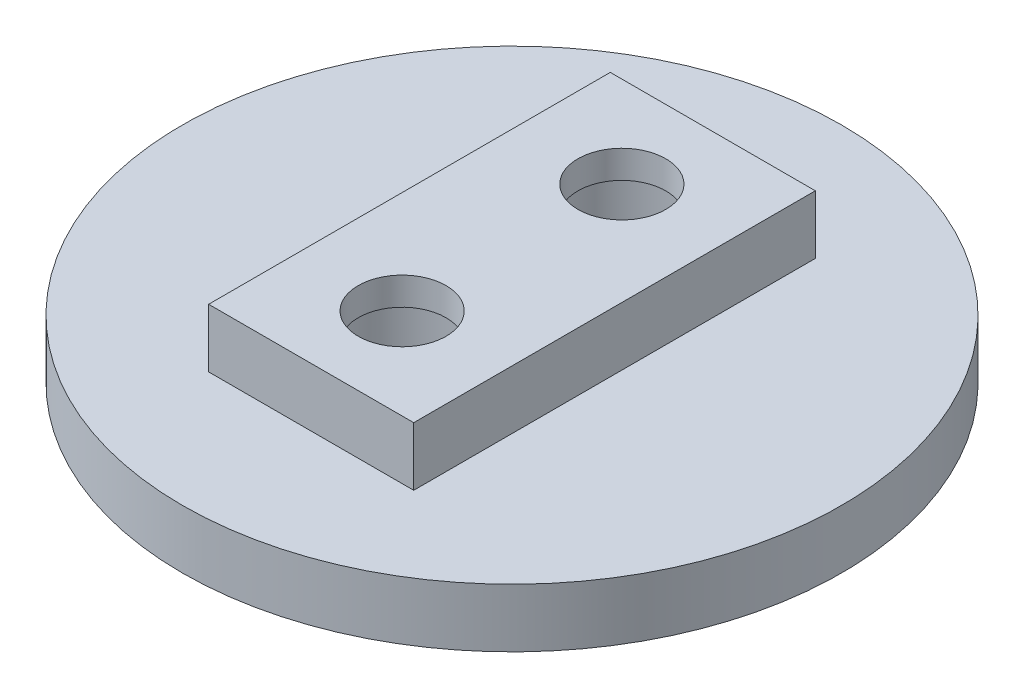
SolidWorks part; units mm, degrees
ref_plane "Front Plane" through (0, 0, 0) normal (0, 0, 1) x (1, 0, 0)
ref_plane "Top Plane" through (0, 0, 0) normal (0, 1, 0) x (1, 0, 0)
ref_plane "Right Plane" through (0, 0, 0) normal (1, 0, 0) x (0, 0, -1)
sketch "Sketch2" plane through (0, 0, 0) normal (0, 1, 0) x (1, 0, 0)
  circle A0 centre (0, 0) radius 22.5
  dimension "D1" = 45
extrude "Boss-Extrude1" add sketch "Sketch2" along normal blind 4
sketch "Sketch3" plane through (0, 4, 0) normal (0, 1, 0) x (1, 0, 0)
  line L1 (-7, -13.71) -> (7, -13.71)
  line L2 (-7, -13.71) -> (-7, 13.71)
  line L3 (-7, 13.71) -> (7, 13.71)
  line L4 (7, -13.71) -> (7, 13.71)
  line L5 (-7, -13.71) -> (7, 13.71) construction
  line L6 (-7, 13.71) -> (7, -13.71) construction
  point P0 (0, 0)
  dimension "D1" = 14
  dimension "D2" = 27.42
extrude "Boss-Extrude2" add sketch "Sketch3" along normal blind 4
sketch "Sketch4" plane through (0, 8, 0) normal (0, 1, 0) x (1, 0, 0)
  line L0 (7, 0) -> (-7, 0) construction
  line L1 (0, 13.71) -> (0, -13.71) construction
  line L2 (-4.3265, 7.5) -> (4.3265, 7.5) construction
  line L3 (-4.3265, -7.5) -> (4.3265, -7.5) construction
  line L4 (7, -13.71) -> (7, 13.71)
  line L16 (7, -13.71) -> (7, 13.71)
  line L20 (7, 13.71) -> (-7, 13.71)
  line L22 (7, 13.71) -> (-7, 13.71)
  line L24 (-7, 13.71) -> (-7, -13.71)
  line L25 (-7, 13.71) -> (-7, -13.71)
  line L26 (-7, -13.71) -> (7, -13.71)
  line L27 (-7, -13.71) -> (7, -13.71)
  circle A0 centre (0, 7.5) radius 3
  circle A1 centre (0, -7.5) radius 3
  point P14 (0, 7.5)
  dimension "D2" = 6
  dimension "D3" = 15
  dimension "D1" = 0
extrude "Cut-Extrude1" cut sketch "Sketch4" against normal through all contours A0 | A1
sketch "Sketch5" plane through (0, 0, 0) normal (0, -1, 0) x (1, 0, 0)
  line L0 (-22.5, 0) -> (22.5, 0) construction
  line L1 (0, 22.5) -> (0, -22.5) construction
  line L2 (-3, 7.5) -> (3, 7.5) construction
  line L3 (-3, -7.5) -> (3, -7.5) construction
  circle A0 centre (0, 7.5) radius 3 construction
  circle A1 centre (0, 0) radius 22.5
  circle A2 centre (0, 0) radius 22.5
  circle A3 centre (0, -7.5) radius 3 construction
  circle A4 centre (0, 7.5) radius 5
  circle A5 centre (0, -7.5) radius 5
  point P17 (0, 7.5)
  point P18 (0, -7.5)
  dimension "D2" = 10
  dimension "D1" = 0
extrude "Cut-Extrude2" cut sketch "Sketch5" against normal blind 6.1 contours A5 | A4
